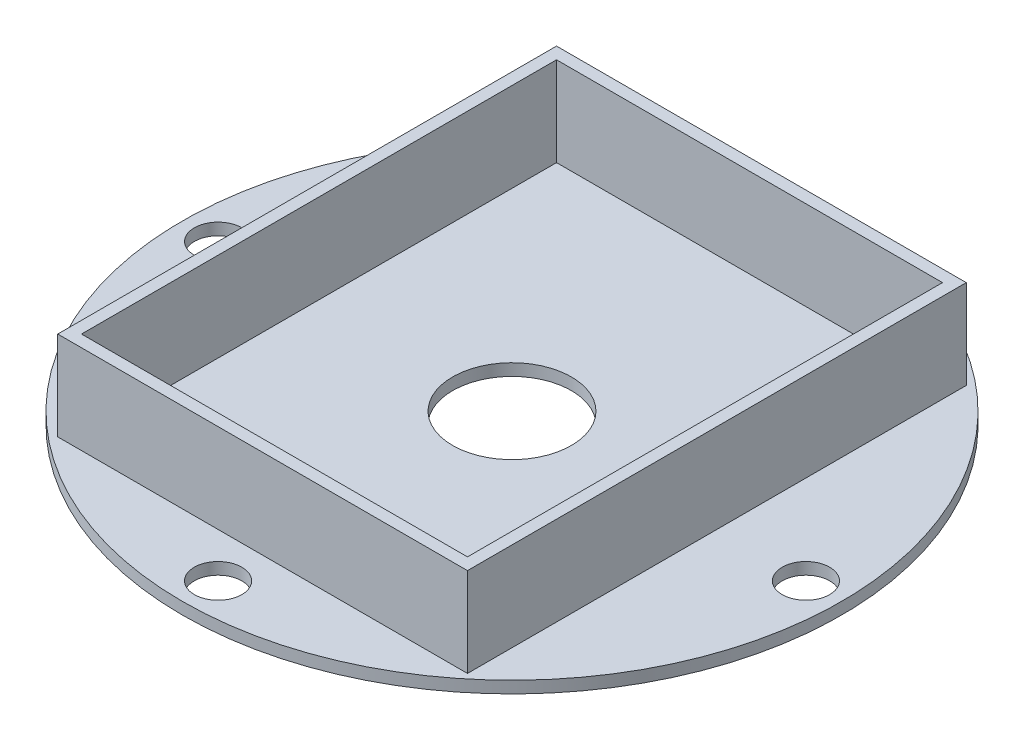
SolidWorks part; units mm, degrees
ref_plane "Front Plane" through (0, 0, 0) normal (0, 0, 1) x (1, 0, 0)
ref_plane "Top Plane" through (0, 0, 0) normal (0, 1, 0) x (1, 0, 0)
ref_plane "Right Plane" through (0, 0, 0) normal (1, 0, 0) x (0, 0, -1)
sketch "Sketch1" plane through (0, 0, 0) normal (0, 1, 0) x (1, 0, 0)
  circle A0 centre (0, 0) radius 55.5
  circle A5 centre (0, 49.5) radius 4
  circle A6 centre (49.5, 0) radius 4
  circle A7 centre (-49.5, 0) radius 4
  circle A8 centre (0, -49.5) radius 4
  dimension "D1" = 111
  dimension "D3" = 8
  dimension "D4" = 8
  dimension "D5" = 8
  dimension "D6" = 8
extrude "Boss-Extrude4" add sketch "Sketch1" along normal blind 2
sketch "Sketch6" plane through (0, 2, 0) normal (0, 1, 0) x (1, 0, 0)
  line L1 (-32.5, 40) -> (32.5, 40)
  line L2 (-32.5, 40) -> (-32.5, -40)
  line L3 (-32.5, -40) -> (32.5, -40)
  line L4 (32.5, 40) -> (32.5, -40)
  line L5 (-32.5, 40) -> (32.5, -40) construction
  line L6 (-32.5, -40) -> (32.5, 40) construction
  line L7 (-34.5, 42) -> (34.5, 42)
  line L8 (-34.5, 42) -> (-34.5, -42)
  line L9 (-34.5, -42) -> (34.5, -42)
  line L10 (34.5, 42) -> (34.5, -42)
  line L11 (-34.5, 42) -> (34.5, -42) construction
  line L12 (-34.5, -42) -> (34.5, 42) construction
  point P0 (0, 0)
  point P6 (0, 0)
  dimension "D1" = 80
  dimension "D2" = 65
  dimension "D3" = 84
  dimension "D4" = 69
extrude "Boss-Extrude5" add sketch "Sketch6" along normal blind 15
sketch "Sketch7" plane through (0, 2, 0) normal (0, 1, 0) x (1, 0, 0)
  circle A0 centre (0, 0) radius 10
  dimension "D1" = 20
extrude "Cut-Extrude2" cut sketch "Sketch7" against normal blind 30
